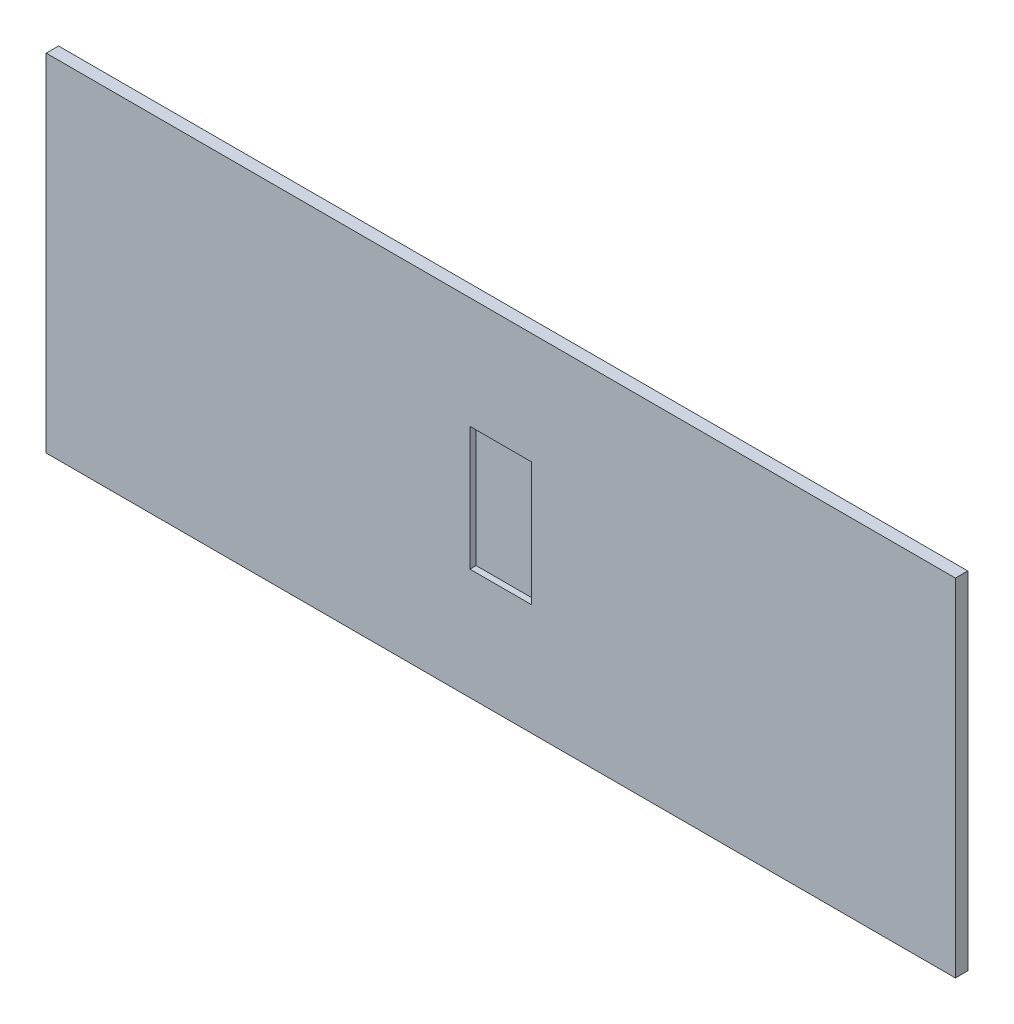
SolidWorks part; units mm, degrees
ref_plane "Plan de face" through (0, 0, 0) normal (0, 0, 1) x (1, 0, 0)
ref_plane "Plan de dessus" through (0, 0, 0) normal (0, 1, 0) x (1, 0, 0)
ref_plane "Plan de droite" through (0, 0, 0) normal (1, 0, 0) x (0, 0, -1)
sketch "Esquisse1" plane through (0, 0, 0) normal (0, 0, 1) x (1, 0, 0)
  line L1 (-73.5, -28) -> (73.5, -28)
  line L2 (-73.5, -28) -> (-73.5, 28)
  line L3 (-73.5, 28) -> (73.5, 28)
  line L4 (73.5, -28) -> (73.5, 28)
  line L5 (-73.5, -28) -> (73.5, 28) construction
  line L6 (-73.5, 28) -> (73.5, -28) construction
  point P0 (0, 0)
  dimension "D1" = 56
  dimension "D2" = 147
extrude "Boss.-Extru.1" add sketch "Esquisse1" along normal mid plane 2
sketch "Esquisse2" plane through (0, 0, 1) normal (0, 0, 1) x (1, 0, 0)
  line L1 (-5, -10) -> (5, -10)
  line L2 (-5, -10) -> (-5, 10)
  line L3 (-5, 10) -> (5, 10)
  line L4 (5, -10) -> (5, 10)
  line L5 (-5, -10) -> (5, 10) construction
  line L6 (-5, 10) -> (5, -10) construction
  point P0 (0, 0)
  dimension "D1" = 20
  dimension "D2" = 10
extrude "Enlèv. mat.-Extru.1" cut sketch "Esquisse2" against normal blind 1
